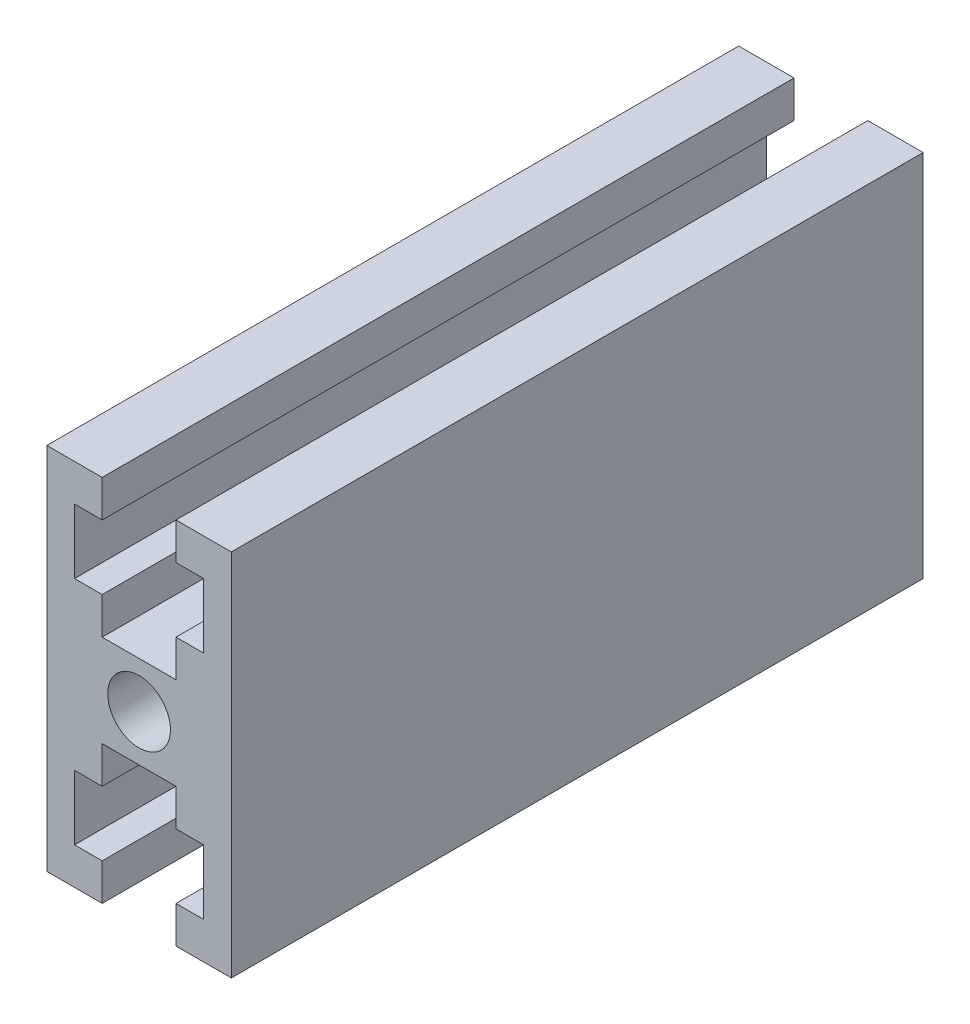
SolidWorks part; units mm, degrees
ref_plane "前视" through (0, 0, 0) normal (0, 0, 1) x (1, 0, 0)
ref_plane "上视" through (0, 0, 0) normal (0, 1, 0) x (1, 0, 0)
ref_plane "右视" through (0, 0, 0) normal (1, 0, 0) x (0, 0, -1)
sketch "草图2" plane through (0, 0, 0) normal (0, 0, 1) x (1, 0, 0)
  line L0 (0, 0) -> (6, 0)
  line L1 (6, 0) -> (6, -4)
  line L2 (6, -4) -> (3, -4)
  line L3 (3, -4) -> (3, -11)
  line L4 (3, -11) -> (6, -11)
  line L5 (6, -11) -> (6, -15)
  line L6 (6, -15) -> (14, -15)
  line L7 (14, -15) -> (14, -11)
  line L8 (14, -11) -> (17, -11)
  line L9 (17, -11) -> (17, -4)
  line L10 (17, -4) -> (14, -4)
  line L11 (14, -4) -> (14, 0)
  line L12 (14, 0) -> (20, 0)
  line L13 (20, 0) -> (20, -40)
  line L14 (0, 0) -> (0, -40)
  line L15 (-88.7936, -20) -> (42.7765, -20) construction
  line L16 (14, -40) -> (20, -40)
  line L17 (14, -36) -> (14, -40)
  line L18 (17, -36) -> (14, -36)
  line L19 (17, -29) -> (17, -36)
  line L20 (14, -29) -> (17, -29)
  line L21 (14, -25) -> (14, -29)
  line L22 (6, -25) -> (14, -25)
  line L23 (6, -29) -> (6, -25)
  line L24 (3, -29) -> (6, -29)
  line L25 (3, -36) -> (3, -29)
  line L26 (6, -36) -> (3, -36)
  line L27 (6, -40) -> (6, -36)
  line L28 (0, -40) -> (6, -40)
  circle A0 centre (10, -20) radius 3.4
  point P23 (0, -20)
  point P24 (20, -20)
  dimension "D1" = 4
  dimension "D11" = 6.8
  dimension "D2" = 7
  dimension "D3" = 14
  dimension "D4" = 8
  dimension "D5" = 6
  dimension "D6" = 6
  dimension "D7" = 3
  dimension "D8" = 4
  dimension "D9" = 20
  dimension "D10" = 10
extrude "凸台-拉伸1" add sketch "草图2" along normal blind 75
